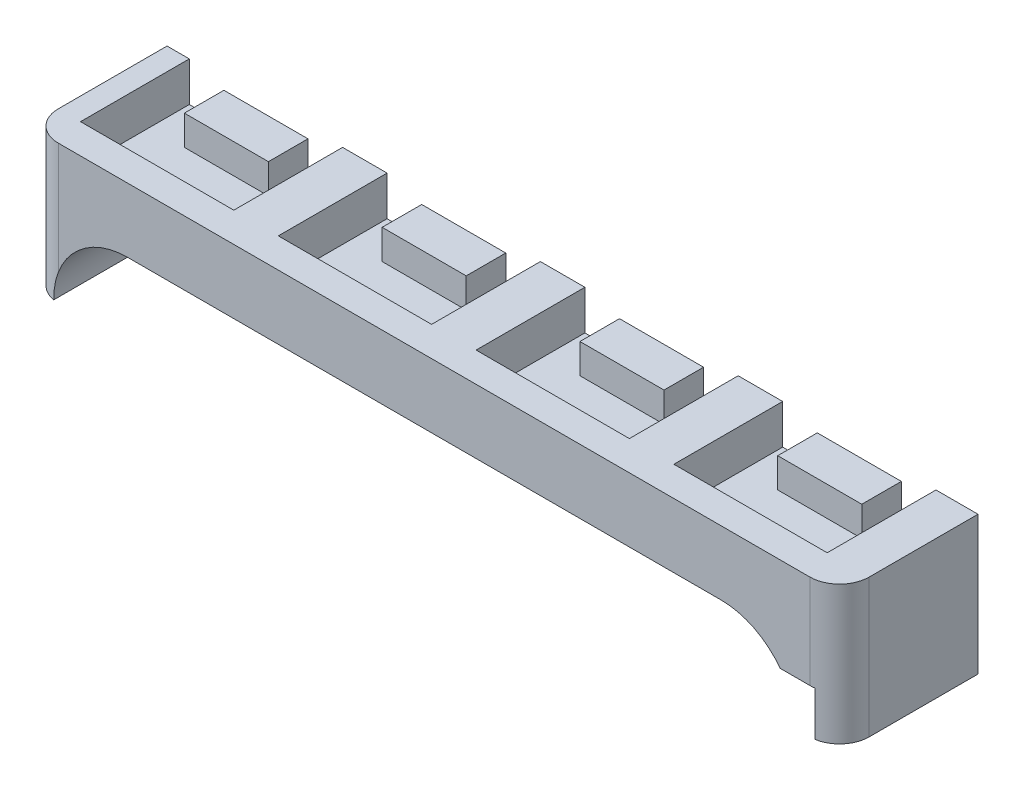
SolidWorks part; units mm, degrees
ref_plane "Alzado" through (0, 0, 0) normal (0, 0, 1) x (1, 0, 0)
ref_plane "Planta" through (0, 0, 0) normal (0, 1, 0) x (1, 0, 0)
ref_plane "Vista lateral" through (0, 0, 0) normal (1, 0, 0) x (0, 0, -1)
sketch "Croquis1" plane through (0, 0, 0) normal (0, 0, 1) x (1, 0, 0)
  line L0 (-38.5, 7.5) -> (-41, 7.5)
  line L1 (-41, 17.5) -> (41, 17.5)
  line L2 (-41, 17.5) -> (-41, -17.5) construction
  line L3 (-41, -17.5) -> (41, -17.5) construction
  line L4 (41, 17.5) -> (41, -17.5) construction
  line L5 (-31, 15) -> (29, 15)
  line L6 (-31, 15) -> (-31, 0) construction
  line L7 (-31, 0) -> (29, 0) construction
  line L8 (29, 15) -> (29, 0) construction
  line L9 (-41, 17.5) -> (-41, 7.5)
  line L10 (38.5, 7.5) -> (41, 7.5)
  line L11 (38.5, 7.5) -> (38.5, 12)
  line L12 (38.5, 12) -> (35, 12)
  line L13 (41, 17.5) -> (41, 7.5)
  circle A0 centre (-31, 7.5) radius 7.5 construction
  arc A1 (-31, 15) -> (-38.5, 7.5) centre (-31, 7.5) ccw
  circle A2 centre (29, 7.5) radius 7.5 construction
  arc A3 (29, 15) -> (35, 12) centre (29, 7.5) cw
  point P4 (0, -17.5)
  point P6 (-41, 0)
  dimension "D4" = 15
  dimension "D1" = 82
  dimension "D2" = 60
  dimension "D3" = 2.5
  dimension "D5" = 10
  dimension "D6" = 2.5
  dimension "D7" = 4.5
extrude "Saliente-Extruir1" add sketch "Croquis1" along normal blind 14
sketch "Croquis2" plane through (0, 0, 0) normal (0, 0, 1) x (1, 0, 0)
  line L0 (41, 17.5) -> (-41, 17.5) construction
  line L1 (33.25, 17.5) -> (24.75, 17.5)
  line L2 (33.25, 17.5) -> (33.25, 20.5)
  line L3 (33.25, 20.5) -> (24.75, 20.5)
  line L4 (24.75, 17.5) -> (24.75, 20.5)
  line L5 (29, 15) -> (29, 17.5) construction
  line L6 (9, 15) -> (9, 17.5) construction
  line L7 (-31, 15) -> (29, 15) construction
  line L8 (-11, 15) -> (-11, 17.5) construction
  line L9 (-31, 15) -> (-31, 17.5) construction
  line L11 (-26.75, 20.5) -> (-35.25, 20.5)
  line L12 (-26.75, 20.5) -> (-26.75, 17.5)
  line L13 (-26.75, 17.5) -> (-35.25, 17.5)
  line L14 (-35.25, 20.5) -> (-35.25, 17.5)
  line L15 (-6.75, 20.5) -> (-15.25, 20.5)
  line L16 (-6.75, 20.5) -> (-6.75, 17.5)
  line L17 (-6.75, 17.5) -> (-15.25, 17.5)
  line L18 (-15.25, 20.5) -> (-15.25, 17.5)
  line L19 (13.25, 20.5) -> (4.75, 20.5)
  line L20 (13.25, 20.5) -> (13.25, 17.5)
  line L21 (13.25, 17.5) -> (4.75, 17.5)
  line L22 (4.75, 20.5) -> (4.75, 17.5)
  point P6 (29, 15)
  point P18 (-31, 17.5)
  point P28 (-11, 17.5)
  point P33 (9, 17.5)
  point P34 (29, 17.5)
  dimension "D1" = 20
  dimension "D2" = 20
  dimension "D3" = 8.5
  dimension "D4" = 3
extrude "Saliente-Extruir2" add sketch "Croquis2" along normal blind 4
sketch "Croquis3" plane through (0, 17.5, 0) normal (0, 1, 0) x (1, 0, 0)
  line L0 (-15.25, -4) -> (-15.25, 0) construction
  line L6 (-41, -14) -> (41, -14)
  line L8 (-38.75, -11) -> (-23.25, -11)
  line L10 (13.25, -4) -> (4.75, -4) construction
  line L11 (41, 0) -> (33.25, 0) construction
  line L12 (36.75, 0) -> (41, 0)
  line L13 (36.75, 0) -> (36.75, -11)
  line L16 (24.75, 0) -> (13.25, 0) construction
  line L17 (16.75, 0) -> (21.25, 0)
  line L18 (16.75, 0) -> (16.75, -11)
  line L20 (21.25, 0) -> (21.25, -11)
  line L23 (4.75, 0) -> (-6.75, 0) construction
  line L24 (-3.25, 0) -> (1.25, 0)
  line L25 (-3.25, 0) -> (-3.25, -11)
  line L27 (1.25, 0) -> (1.25, -11)
  line L29 (-15.25, 0) -> (-26.75, 0) construction
  line L30 (-23.25, 0) -> (-18.75, 0)
  line L31 (-23.25, 0) -> (-23.25, -11)
  line L33 (-18.75, 0) -> (-18.75, -11)
  line L36 (-41, 0) -> (-38.75, 0)
  line L39 (-38.75, 0) -> (-38.75, -11)
  line L40 (-18.75, -11) -> (-3.25, -11)
  line L41 (21.25, -11) -> (36.75, -11)
  line L42 (1.25, -11) -> (16.75, -11)
  line L43 (41, 0) -> (41, -14)
  line L44 (-41, 0) -> (-41, -14)
  line L45 (41, -14) -> (41, 0) construction
  line L47 (-35.25, -4) -> (-35.25, 0) construction
  dimension "D1" = 7
  dimension "D2" = 3.5
  dimension "D3" = 3.5
  dimension "D8" = 15.5
extrude "Saliente-Extruir3" add sketch "Croquis3" along normal blind 4
fillet "Redondeo1" radius 3 2 edges at (-41, 14.5, 14) (41, 14.5, 14)
